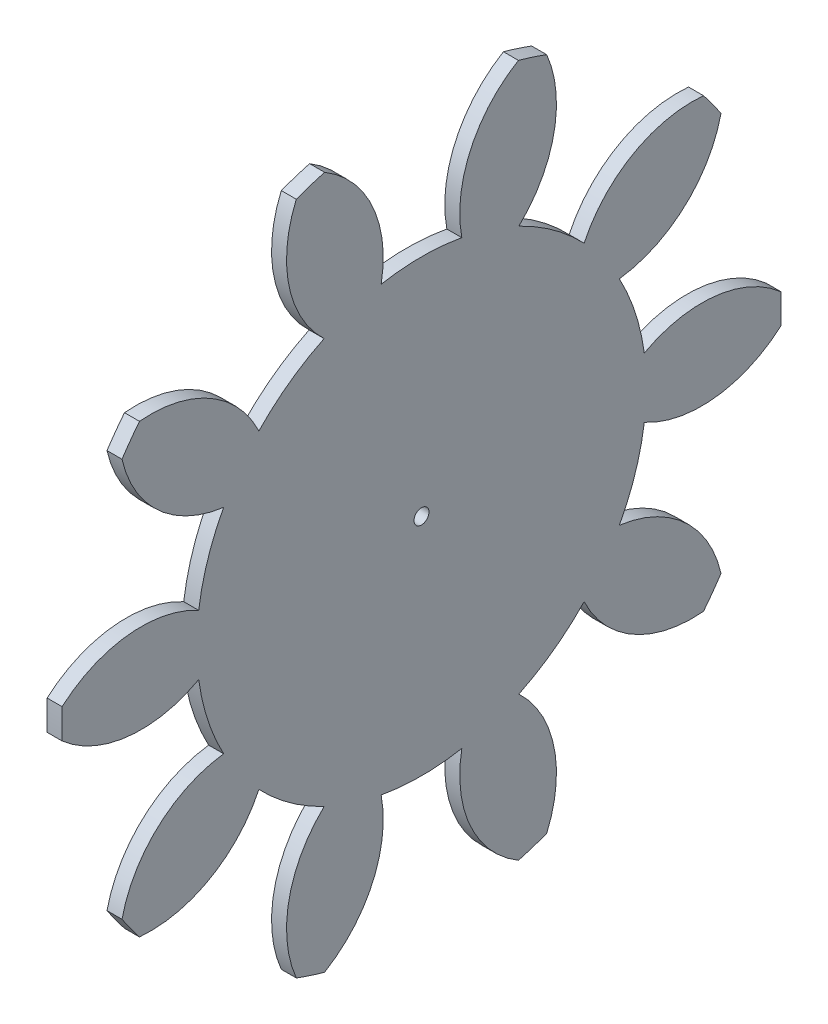
SolidWorks part; units mm, degrees
ref_plane "Plane1" through (0, 0, 0) normal (0, 0, 1) x (1, 0, 0)
ref_plane "Plane2" through (0, 0, 0) normal (0, 1, 0) x (1, 0, 0)
ref_plane "Plane3" through (0, 0, 0) normal (1, 0, 0) x (0, 0, -1)
sketch "HoldingSke" plane through (0, 0, 0) normal (0, 1, 0) x (1, 0, 0)
  line L0 (0, 0) -> (0.2462, -0.0434)
  line L1 (-15, 0) -> (100, 0) construction
  line L2 (0, 0) -> (-2.1039, 2.3779)
  line L3 (0, 0) -> (-11.863, 4.5341)
  line L4 (0, 0) -> (8.5048, 1.4996)
  line L5 (0, 0) -> (-46.8476, -17.4728)
  line L6 (0, 0) -> (-0.829, -0.5593)
  line L7 (-2.1039, 2.3779) -> (8.6586, 51.2059)
  line L8 (-76.2, 54.61) -> (-76.1, 54.61)
  line L9 (-67.7845, 28.3722) -> (-49.3413, 33.142)
  line L10 (-76.2, 71.12) -> (104.1128, 71.12)
  line L11 (0, 0) -> (-1, 0)
  line L12 (-76.2, 101.6) -> (-76.073, 101.6)
  line L13 (24.9733, 27.94) -> (52.9518, 28.4284)
  line L14 (24.9733, 27.94) -> (24.9743, 27.94)
  line L15 (24.9733, 27.94) -> (100.4006, 29.5858)
  line L16 (-63.627, -4) -> (-12.827, -4)
  circle A0 centre (0, 0) radius 0.5
  circle A1 centre (0, 0) radius 14.999
  circle A2 centre (0, 0) radius 37.5
  circle A3 centre (0, 0) radius 0.5
  dimension "MHD" = 29.998
  dimension "Hub_dia" = 75
  dimension "Bore" = 1
  dimension "MBD" = 1
  dimension "Num_teeth" = 10
  dimension "Pitch" = 0.25
  dimension "Overall_len" = 50
  dimension "Show_teeth" = 10
  dimension "Thickness" = 1
  dimension "OAL" = 50.0001
  dimension "T_dim" = 0.1
  dimension "Ap" = 14.5
  dimension "H" = 19.05
  dimension "Pitch_radius" = 180.3128
  dimension "Width" = 1
  dimension "Backlash" = 0.127
  dimension "Addendum_fac" = 1
  dimension "Dedendum_fac" = 1.25
  dimension "Clearance_fac" = 0.25
  dimension "Dedendum_add" = 0.001
  dimension "Module" = 4
sketch "BasProSke" plane through (0, 0, 0) normal (0, 1, 0) x (1, 0, 0)
  line L0 (-10, 0) -> (60, 0) construction
  line L1 (0, 0) -> (0, 24)
  line L2 (0, 0) -> (1, 0)
  line L3 (1, 0) -> (1, 24)
  line L4 (1, 24) -> (0, 24)
  dimension "Thickness" = 1
  dimension "Diameter" = 48
revolve "Base-Revolve" add sketch "BasProSke" angle 360 about L0
sketch "TooCutSke" plane through (0, 0, 0) normal (1, 0, 0) x (0, 0, -1)
  line L1 (0, 0) -> (0, 107) construction
  line L2 (0, 0) -> (-3.3505, 19.7173) construction
  line L3 (0, 0) -> (-12.2295, 37.6384) construction
  line L4 (-3.3505, 19.7173) -> (-6.1147, 18.8192) construction
  arc A0 (2.6906, 14.7557) -> (-2.6906, 14.7557) centre (0, 0) ccw
  arc A1 (6.4968, 23.1303) -> (-6.4968, 23.1303) centre (0, 0) ccw
  circle A2 centre (0, 0) radius 20 construction
  circle A3 centre (0, 0) radius 19.363 construction
  arc A4 (-2.6906, 14.7557) -> (-6.4968, 23.1303) centre (-10.5527, 16.2347) ccw
  arc A5 (6.4968, 23.1303) -> (2.6906, 14.7557) centre (10.5527, 16.2347) ccw
  dimension "Root_dia" = 29.998
  dimension "Overcut_dia" = 48.0508
  dimension "Pitch_dia" = 40
  dimension "Base_dia" = 38.7259
  dimension "Flank_rad" = 8
  dimension "Half_ang" = 18
  dimension "Half_CT" = 2.9064
extrude "ToothCut" cut sketch "TooCutSke" along normal through all
fillet "Breaks" [suppressed] radius 0.08
fillet "RootFillets" [suppressed] radius 1.001
pattern_circular "TeethCuts" count 10 every 36 about axis through (-10, 0, 0) along (1, 0, 0) of "ToothCut", "RootFillets", "Breaks"
sketch "HubNeaOneSke" plane through (0, 0, 0) normal (-1, 0, 0) x (0, 0, 1)
  circle A0 centre (0, 0) radius 14.999
  dimension "Diameter" = 29.998
extrude "HubNearOne" [suppressed] add sketch "HubNeaOneSke" along normal blind 49.0001
sketch "HubNeaBotSke" plane through (0, 0, 0) normal (-1, 0, 0) x (0, 0, 1)
  circle A0 centre (0, 0) radius 14.999
  dimension "Diameter" = 29.998
extrude "HubNearBoth" [suppressed] add sketch "HubNeaBotSke" along normal blind 24.5
ref_plane "FarPln" through (1, 0, 0) normal (1, 0, 0) x (0, 0, -1)
sketch "HubFarSke" plane through (1, 0, 0) normal (1, 0, 0) x (0, 0, -1)
  circle A0 centre (0, 0) radius 14.999
  dimension "Diameter" = 29.998
extrude "HubFar" [suppressed] add sketch "HubFarSke" along normal blind 24.5
sketch "BorSke" plane through (0, 0, 0) normal (1, 0, 0) x (0, 0, -1)
  circle A0 centre (0, 0) radius 0.5
  dimension "Diameter" = 1
extrude "Bore" cut sketch "BorSke" along normal mid plane 100.0001
sketch "KeySke" plane through (0, 0, 0) normal (1, 0, 0) x (0, 0, -1)
  line L0 (-0.05, 0) -> (-0.05, 0.6)
  line L1 (-0.05, 0.6) -> (0.05, 0.6)
  line L2 (0.05, 0.6) -> (0.05, 0)
  line L3 (0, 0) -> (0, 34) construction
  line L4 (-0.05, 0) -> (0.05, 0)
  dimension "Offset" = 0.6
extrude "Keyway" [suppressed] cut sketch "KeySke" along normal mid plane 100.0001
pattern_circular "Keyway2" [suppressed] count 2 every 90 about axis through (-10, 0, 0) along (1, 0, 0)
equation "' \"Module@HoldingSke\" = 6.35"
equation "' \"Num_teeth@HoldingSke\" = 12"
equation "' \"Ap@HoldingSke\" =  20"
equation "' \"Ap@HoldingSke\" = 20"
equation "' \"Width@HoldingSke\" = 0.5 * 25.4"
equation "' \"Hub_dia@HoldingSke\"= 1 * 25.4"
equation "' \"Hub_dia@HoldingSke\" = 1 * 25.4"
equation "' \"Overall_len@HoldingSke\" = 1.0 * 25.4"
equation "' \"Bore@HoldingSke\" = 0.75 * 25.4"
equation "' \"T_dim@HoldingSke\" = 0.1 * 25.4"
equation "' \"Width@KeySke\" = 0.25 * 25.4"
equation "' \"Show_teeth@HoldingSke\" = 13"
equation "' \"Backlash@HoldingSke\" = 0.009 * 25.4"
equation "' \"Addendum_fac@HoldingSke\" = 1.0"
equation "' \"Dedendum_fac@HoldingSke\" = 1.25"
equation "' \"Dedendum_add@HoldingSke\" = 0.00005 * 25.4"
equation "' \"Clearance_fac@HoldingSke\" = 0.25"
equation "\"Pitch@HoldingSke\" = 1 / \"Module@HoldingSke\""
equation "\"Overcut_dia@TooCutSke\" = (\"Num_teeth@HoldingSke\" + 2 * \"Addendum_fac@HoldingSke\") / \"Pitch@HoldingSke\" + 0.002 * 25.4"
equation "\"Pitch_dia@TooCutSke\" = \"Num_teeth@HoldingSke\" / \"Pitch@HoldingSke\""
equation "\"Base_dia@TooCutSke\" = \"Num_teeth@HoldingSke\" / \"Pitch@HoldingSke\" * cos((\"Ap@HoldingSke\"  * 3.14159265 / 180))"
equation "\"Root_dia@TooCutSke\" = (\"Num_teeth@HoldingSke\" + 2) / \"Pitch@HoldingSke\" - 2 * (\"Addendum_fac@HoldingSke\" + \"Dedendum_fac@HoldingSke\") / \"Pitch@HoldingSke\" - \"Dedendum_add@HoldingSke\" * 2"
equation "\"Half_ang@TooCutSke\" = 180 / \"Num_teeth@HoldingSke\""
equation "\"Half_CT@TooCutSke\" = \"Num_teeth@HoldingSke\" / \"Pitch@HoldingSke\" * sin((3.14159265 / 2 / \"Num_teeth@HoldingSke\")) / 2 - 7 * \"Backlash@HoldingSke\" / 4"
equation "\"Flank_rad@TooCutSke\" = \"Num_teeth@HoldingSke\" / \"Pitch@HoldingSke\" / 5"
equation "\"Radius@RootFillets\" = \"Clearance_fac@HoldingSke\" / \"Pitch@HoldingSke\" + \"Dedendum_add@HoldingSke\""
equation "\"Break_rad@Breaks\" = 0.02 / \"Pitch@HoldingSke\""
equation "\"Thickness@HoldingSke\" = \"Width@HoldingSke\""
equation "\"OAL@HoldingSke\" = \"Thickness@HoldingSke\""
equation "\"MHD@HoldingSke\" = (\"Num_teeth@HoldingSke\" + 2) / \"Pitch@HoldingSke\" - 2 * (\"Addendum_fac@HoldingSke\" + \"Dedendum_fac@HoldingSke\")  / \"Pitch@HoldingSke\" - \"Dedendum_add@HoldingSke\" * 2"
equation "\"MBD@HoldingSke\" = (\"Num_teeth@HoldingSke\" + 2) / \"Pitch@HoldingSke\" - 2 * (\"Addendum_fac@HoldingSke\" + \"Dedendum_fac@HoldingSke\")  / \"Pitch@HoldingSke\" - \"Dedendum_add@HoldingSke\" * 2 - 0.002 * 25.4"
equation "\"MHD@HoldingSke\" = ((sgn( \"MHD@HoldingSke\" - \"Hub_dia@HoldingSke\" )-1)*( \"MHD@HoldingSke\" - \"Hub_dia@HoldingSke\" ))/-2+ \"Hub_dia@HoldingSke\""
equation "\"MBD@HoldingSke\" = ((sgn( \"MBD@HoldingSke\" - \"Bore@HoldingSke\" )-1)*( \"MBD@HoldingSke\" - \"Bore@HoldingSke\" ))/-2+ \"Bore@HoldingSke\""
equation "\"OAL@HoldingSke\" = ((sgn( \"OAL@HoldingSke\" - \"Overall_len@HoldingSke\" )+1)*( \"OAL@HoldingSke\" - \"Overall_len@HoldingSke\" ))/2 + \"Overall_len@HoldingSke\" + 0.000002 * 25.4"
equation "\"Num_teeth@TeethCuts\" = int( \"Show_teeth@HoldingSke\" ) + 1"
equation "\"Num_teeth@TeethCuts\" = ((sgn( \"Num_teeth@TeethCuts\" - \"Num_teeth@HoldingSke\" )-1)*( \"Num_teeth@TeethCuts\" - \"Num_teeth@HoldingSke\" ))/-2+ \"Num_teeth@HoldingSke\""
equation "\"Num_teeth@TeethCuts\" = ((sgn( \"Num_teeth@TeethCuts\" - 2.0)+1)*( \"Num_teeth@TeethCuts\" - 2.0))/2 +2.0"
equation "\"Angle@TeethCuts\" = 360.0 / \"Num_teeth@HoldingSke\""
equation "\"Diameter@BasProSke\" = (\"Num_teeth@HoldingSke\" + 2 * \"Addendum_fac@HoldingSke\") / \"Pitch@HoldingSke\""
equation "\"Thickness@BasProSke\"  = \"Thickness@HoldingSke\""
equation "' \"Fillet_rad@BasProSke\" =  \"Thickness@HoldingSke\" * 0.05"
equation "' \"Fillet_rad@BasProSke\" = \"Thickness@HoldingSke\" * 0.05"
equation "\"MHD@HoldingSke\" = ((sgn( \"MHD@HoldingSke\" - \"Root_dia@TooCutSke\" )-1)*( \"MHD@HoldingSke\" - \"Root_dia@TooCutSke\" ))/-2+ \"Root_dia@TooCutSke\""
equation "\"Diameter@HubNeaOneSke\" = \"MHD@HoldingSke\""
equation "\"Length@HubNearOne\" = \"OAL@HoldingSke\" - \"Thickness@BasProSke\""
equation "\"Diameter@HubNeaBotSke\" = \"MHD@HoldingSke\""
equation "\"Length@HubNearBoth\" = ( \"OAL@HoldingSke\" - \"Thickness@BasProSke\" ) / 2.0"
equation "\"Thickness@FarPln\" = \"Thickness@BasProSke\""
equation "\"Diameter@HubFarSke\" = \"MHD@HoldingSke\""
equation "\"Length@HubFar\" = ( \"OAL@HoldingSke\" - \"Thickness@BasProSke\" ) / 2.0"
equation "\"Diameter@BorSke\" = \"MBD@HoldingSke\""
equation "\"D1@Bore\" = \"OAL@HoldingSke\" * 2.0"
equation "\"D1@Keyway\" = \"OAL@HoldingSke\" * 2.0"
equation "\"Offset@KeySke\" = \"T_dim@HoldingSke\" + \"MBD@HoldingSke\" / 2.0"
